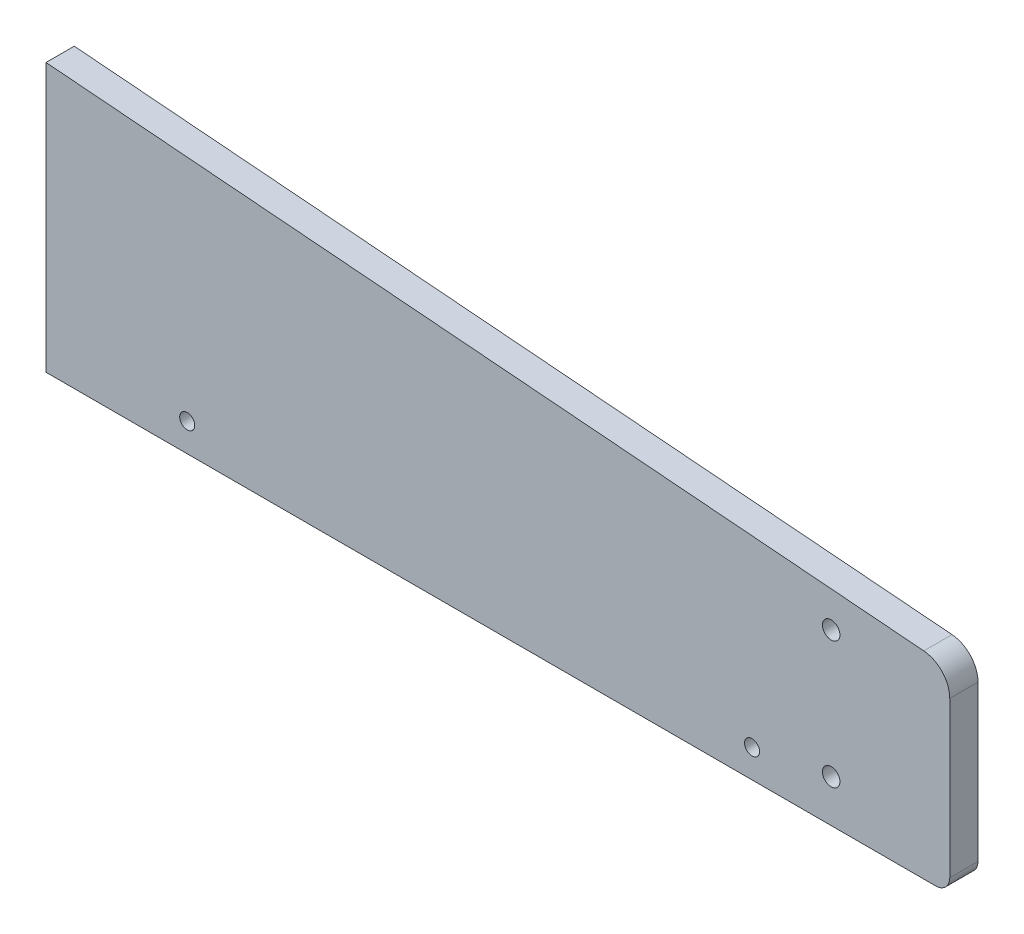
SolidWorks part; units mm, degrees
material "PE High Density"
ref_plane "Front Plane" through (0, 0, 0) normal (0, 0, 1) x (1, 0, 0)
ref_plane "Top Plane" through (0, 0, 0) normal (0, 1, 0) x (1, 0, 0)
ref_plane "Right Plane" through (0, 0, 0) normal (1, 0, 0) x (0, 0, -1)
sketch "Sketch1" plane through (0, 0, 0) normal (0, 0, 1) x (1, 0, 0)
  line L0 (63.5, 0) -> (63.5, 120.65)
  line L1 (0, 0) -> (1219.2, 0) construction
  line L2 (0, 0) -> (0, 1778) construction
  line L3 (0, 1778) -> (1219.2, 1778) construction
  line L4 (1219.2, 0) -> (1219.2, 1778) construction
  line L5 (63.5, 120.65) -> (458.2196, 88.859)
  line L6 (469.9, 76.2) -> (469.9, 0)
  line L7 (469.9, 0) -> (63.5, 0)
  circle A0 centre (609.6, 241.3) radius 241.3 construction
  arc A1 (469.9, 76.2) -> (458.2196, 88.859) centre (457.2, 76.2) ccw
  dimension "D3" = 609.6
  dimension "D4" = 482.6
  dimension "D10" = 12.7
  dimension "D1" = 1219.2
  dimension "D2" = 1778
  dimension "D5" = 241.3
  dimension "D6" = 63.5
  dimension "D7" = 406.4
  dimension "D8" = 76.2
  dimension "D9" = 120.65
  dimension "D11" = 4.605
extrude "Boss-Extrude1" add sketch "Sketch1" along normal blind 12.7
sketch "Sketch2" plane through (0, 0, 12.7) normal (0, 0, 1) x (1, 0, 0)
  line L0 (63.5, 0) -> (469.9, 0) construction
  line L1 (63.5, 120.65) -> (63.5, 0) construction
  circle A0 centre (127, 12.7) radius 3.3782
  circle A1 centre (381, 12.7) radius 3.3782
  dimension "D1" = 12.7
  dimension "D4" = 6.7564
  dimension "D2" = 63.5
  dimension "D3" = 254
extrude "Cut-Extrude1" cut sketch "Sketch2" against normal through all
fillet "Fillet1" radius 6.35 1 edges at (469.9, 0, 6.35)
sketch "Sketch4" plane through (0, 0, 0) normal (0, 0, -1) x (-1, 0, 0)
  line L0 (-469.9, 6.35) -> (-469.9, 76.2) construction
  line L1 (-63.5, 0) -> (-463.55, 0) construction
  circle A0 centre (-416.5676, 76.2) radius 3.937
  circle A1 centre (-416.5676, 19.05) radius 3.937
  dimension "D4" = 7.874
  dimension "D1" = 57.15
  dimension "D2" = 53.3324
  dimension "D3" = 19.05
extrude "Cut-Extrude2" cut sketch "Sketch4" against normal through all
